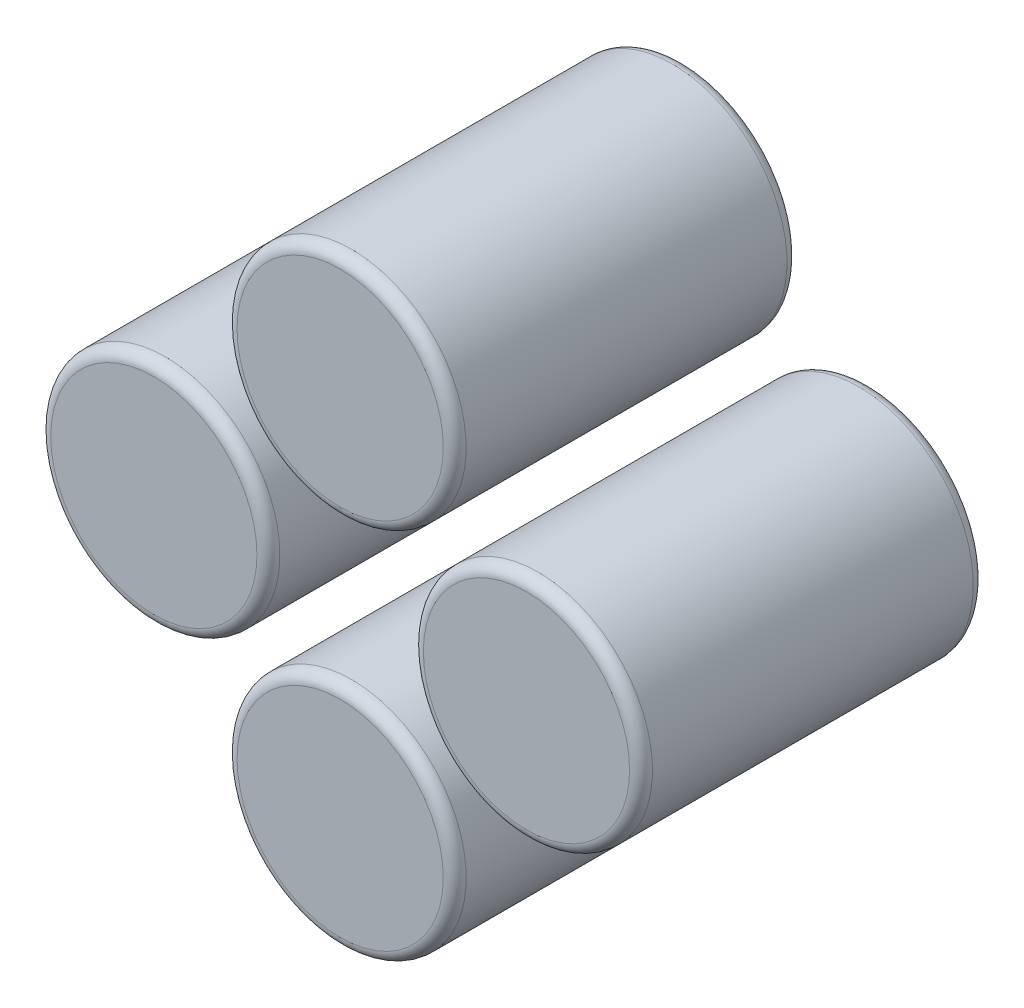
SolidWorks part; units mm, degrees
ref_plane "Front Plane" through (0, 0, 0) normal (0, 0, 1) x (1, 0, 0)
ref_plane "Top Plane" through (0, 0, 0) normal (0, 1, 0) x (1, 0, 0)
ref_plane "Right Plane" through (0, 0, 0) normal (1, 0, 0) x (0, 0, -1)
sketch "草图1" plane through (-51, 0, 0) normal (0, 0, -1) x (-1, 0, 0)
  line L0 (-59.1317, 0) -> (-51, -8.1317) construction
  line L1 (-51, -8.1317) -> (-42.8683, 0) construction
  line L2 (-42.8683, 0) -> (-51, 8.1317) construction
  line L3 (-51, 8.1317) -> (-59.1317, 0) construction
  line L4 (-59.1317, 0) -> (-42.8683, 0) construction
  circle A8 centre (-42.8683, 0) radius 5
  circle A9 centre (-51, -8.1317) radius 5
  circle A10 centre (-51, 8.1317) radius 5
  circle A11 centre (-59.1317, 0) radius 5
  dimension "D1" = 10
  dimension "D2" = 11.5
extrude "凸台-拉伸1" add sketch "草图1" along normal mid plane 15
fillet "圆角1" radius 0.5 2 edges at (3.1317, 0, 7.5) (3.1317, 0, -7.5)
fillet "圆角2" radius 0.5 2 edges at (-5, -8.1317, 7.5) (-5, -8.1317, -7.5)
fillet "圆角3" radius 0.5 2 edges at (-5, 8.1317, 7.5) (-5, 8.1317, -7.5)
fillet "圆角4" radius 0.5 2 edges at (-13.1317, 0, 7.5) (-13.1317, 0, -7.5)
